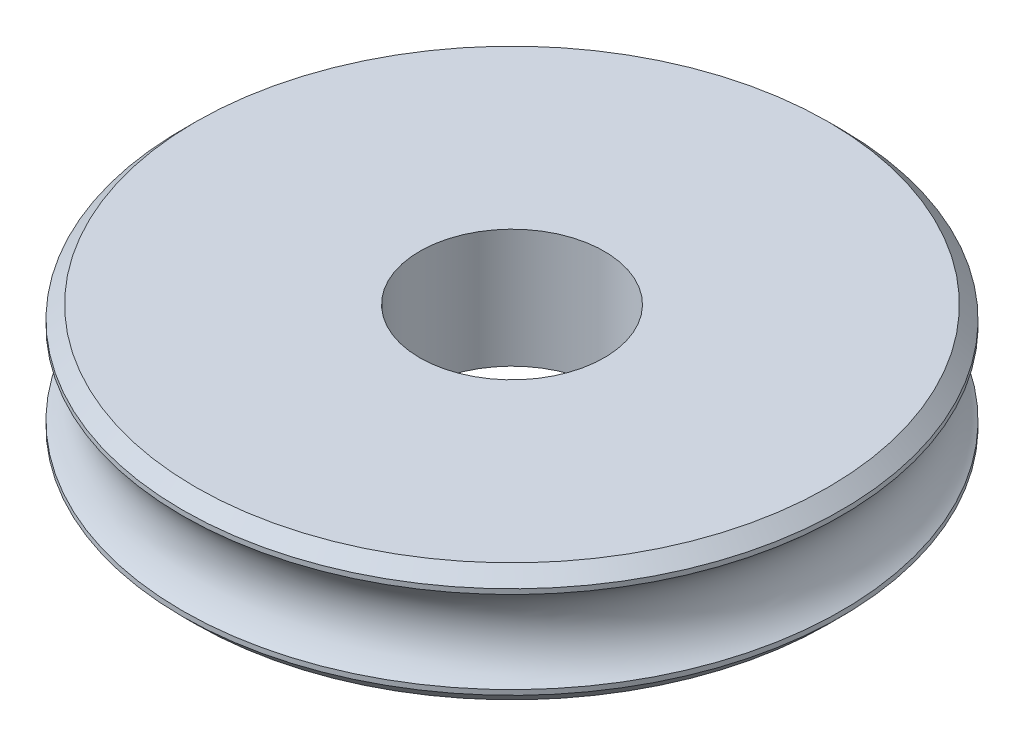
SolidWorks part; units mm, degrees
material "Zinc AC41A Alloy, As Cast"
ref_plane "Plan de face" through (0, 0, 0) normal (0, 0, 1) x (1, 0, 0)
ref_plane "Plan de dessus" through (0, 0, 0) normal (0, 1, 0) x (1, 0, 0)
ref_plane "Plan de droite" through (0, 0, 0) normal (1, 0, 0) x (0, 0, -1)
sketch "Sketch2" plane through (0, 0, 0) normal (0, 0, 1) x (1, 0, 0)
  line L0 (0, 0) -> (0, -1.75) construction
  line L1 (0, 0) -> (13.75, 0) construction
  line L2 (3.5, 2.25) -> (3.5, -2.25)
  line L4 (12.5, -1.75) -> (12.5, -1.5612)
  line L5 (3.5, -2.25) -> (12, -2.25)
  line L6 (12, -2.25) -> (12.5, -1.75)
  line L7 (12, 2.25) -> (12.5, 1.75)
  line L8 (3.5, 2.25) -> (12, 2.25)
  line L9 (12.5, 1.75) -> (12.5, 1.5612)
  arc A1 (12.5, 1.5612) -> (12.5, -1.5612) centre (13.75, 0) ccw
  point P14 (3.5, 0)
  dimension "D3" = 3.5
  dimension "D4" = 12.5
  dimension "D5" = 2
  dimension "D1" = 2.25
  dimension "D2" = 13.75
  dimension "D7" = 0.5
  dimension "D8" = 0.5
revolve "Revolve2" add sketch "Sketch2" angle 360 about L0
